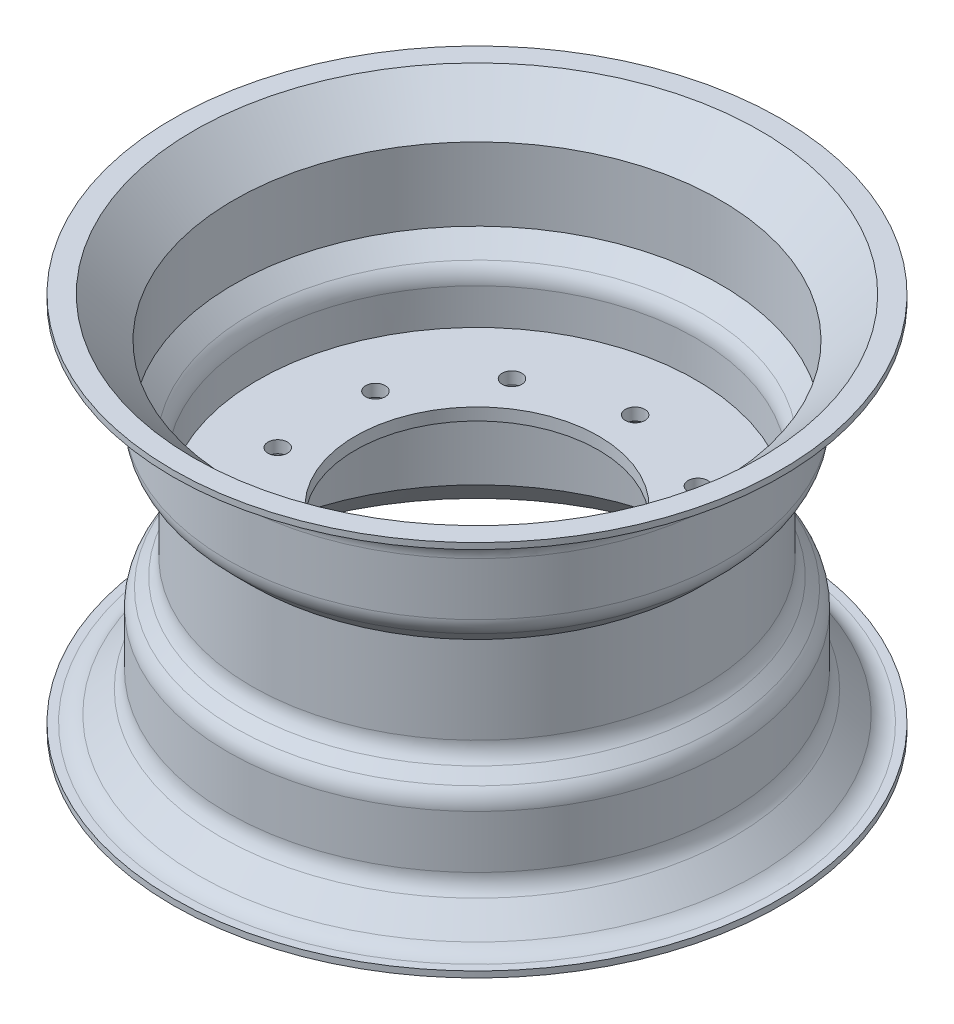
SolidWorks part; units mm, degrees
ref_plane "Front Plane" through (0, 0, 0) normal (0, 0, 1) x (1, 0, 0)
ref_plane "Top Plane" through (0, 0, 0) normal (0, 1, 0) x (1, 0, 0)
ref_plane "Right Plane" through (0, 0, 0) normal (1, 0, 0) x (0, 0, -1)
sketch "Sketch1" plane through (0, 0, 0) normal (0, 0, 1) x (1, 0, 0)
  line L0 (0, 200.8318) -> (0, -169.3828) construction
  line L1 (-390.6451, 0) -> (159.9798, 0) construction
  line L2 (-250, 150) -> (-235, 150)
  line L3 (-235, 150) -> (-205, 120)
  line L4 (-205, 120) -> (-205, 60)
  line L5 (-205, 60) -> (-185, 40)
  line L6 (-185, 40) -> (-185, -40)
  line L7 (-205, -60) -> (-185, -40)
  line L8 (-205, -120) -> (-205, -60)
  line L9 (-235, -150) -> (-205, -120)
  line L10 (-250, -150) -> (-235, -150)
  line L11 (-250, 155) -> (-232.9289, 155)
  line L12 (-232.9289, 155) -> (-200, 122.0711)
  line L13 (-200, 122.0711) -> (-200, 62.0711)
  line L14 (-200, 62.0711) -> (-180, 42.0711)
  line L15 (-180, 42.0711) -> (-180, 4.1023)
  line L16 (-200, -62.0711) -> (-180, -42.0711)
  line L17 (-200, -122.0711) -> (-200, -62.0711)
  line L18 (-232.9289, -155) -> (-200, -122.0711)
  line L19 (-250, -155) -> (-232.9289, -155)
  line L20 (-250, 155) -> (-250, 150)
  line L21 (-250, -150) -> (-250, -155)
  line L22 (-180, 4.1023) -> (-100, 4.1023)
  line L23 (-180, -5.8977) -> (-100, -5.8977)
  line L24 (-100, 4.1023) -> (-100, -5.8977)
  line L25 (-180, -5.8977) -> (-180, -42.0711)
  line L27 (-180, 42.0711) -> (-180, -42.0711) construction
  point P13 (-185, 0)
  dimension "D1" = 135
  dimension "D2" = 135
  dimension "D3" = 5
  dimension "D4" = 100
  dimension "D5" = 15
  dimension "D6" = 30
  dimension "D7" = 60
  dimension "D8" = 20
  dimension "D9" = 40
  dimension "D10" = 250
  dimension "D11" = 10
revolve "Revolve1" add sketch "Sketch1" angle 360 about L0
sketch "Sketch2" plane through (0, 4.1023, 0) normal (0, 1, 0) x (1, 0, 0)
  circle A0 centre (0, 130) radius 8
  dimension "D2" = 16
  dimension "D1" = 130
fillet "Fillet1" radius 20 8 edges at (0, 150, 235) (0, -150, 235) (0, 42.0711, 180) (0, -120, 205) (0, -60, 205) (0, -40, 185) (0, 60, 205) (0, 120, 205)
extrude "Cut-Extrude1" cut sketch "Sketch2" against normal blind 20 contours A0
pattern_circular "CirPattern1" count 10 over 360 about axis through (0, 0, 0) along (0, 1, 0) of "Cut-Extrude1"
